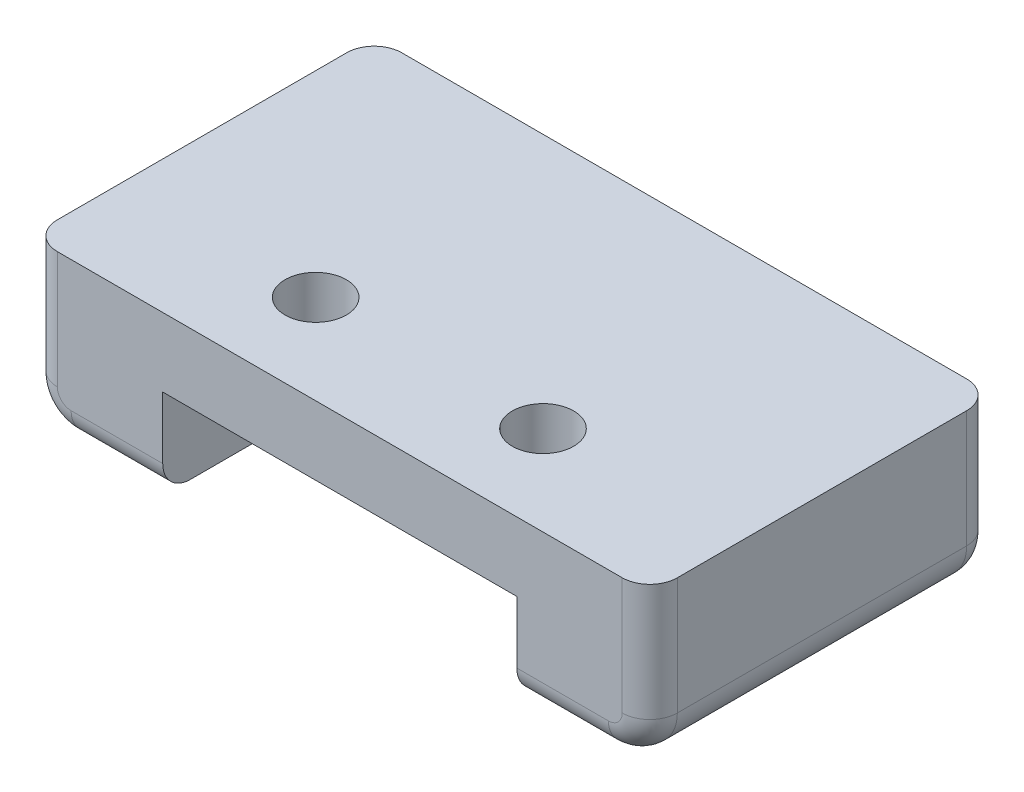
SolidWorks part; units mm, degrees
material "ABS"
ref_plane "Front Plane" through (0, 0, 0) normal (0, 0, 1) x (1, 0, 0)
ref_plane "Top Plane" through (0, 0, 0) normal (0, 1, 0) x (1, 0, 0)
ref_plane "Right Plane" through (0, 0, 0) normal (1, 0, 0) x (0, 0, -1)
sketch "Sketch1" plane through (0, 0, 0) normal (0, 0, 1) x (1, 0, 0)
  line L0 (-22.5, 5) -> (22.5, 5)
  line L1 (22.5, 5) -> (22.5, -6.5)
  line L2 (22.5, -6.5) -> (12.85, -6.5)
  line L3 (12.85, -6.5) -> (12.85, 0)
  line L4 (12.85, 0) -> (-12.85, 0)
  line L5 (-12.85, 0) -> (-12.85, -6.5)
  line L6 (-12.85, -6.5) -> (-22.5, -6.5)
  line L7 (-22.5, -6.5) -> (-22.5, 5)
  line L8 (0, 0) -> (0, 5) construction
  dimension "D1" = 5
  dimension "D2" = 25.7
  dimension "D3" = 45
  dimension "D4" = 6.5
extrude "Boss-Extrude1" add sketch "Sketch1" along normal blind 25
sketch "Sketch2" plane through (0, 5, 0) normal (0, 1, 0) x (1, 0, 0)
  line L0 (0, 0) -> (0, -25) construction
  line L1 (22.5, 0) -> (-22.5, 0) construction
  line L2 (22.5, -25) -> (-22.5, -25) construction
  circle A0 centre (-8.25, -18.5) radius 2.225
  circle A1 centre (8.25, -18.5) radius 2.225
  point P10 (0, -12.5)
  dimension "D1" = 4.45
  dimension "D2" = 16.5
  dimension "D3" = 6
extrude "Cut-Extrude1" cut sketch "Sketch2" against normal through all
fillet "Fillet1" radius 3 2 edges at (22.5, -6.5, 12.5) (-22.5, -6.5, 12.5)
fillet "Fillet2" radius 2 12 edges at (16.175, -6.5, 25) (21.6213, -5.6213, 25) (-16.175, -6.5, 25) (-21.6213, -5.6213, 25) (-16.175, -6.5, 0) (-21.6213, -5.6213, 0) (16.175, -6.5, 0) (21.6213, -5.6213, 0) (22.5, 0.75, 25) (-22.5, 0.75, 25) (-22.5, 0.75, 0) (22.5, 0.75, 0)
equation "\"D2@Sketch1\"=25.5mm+\"print_fit@Parameters@Parameters.SLDPRT\""
equation "\"D1@Sketch2\"=4.00mm+\"print_free@Parameters@Parameters.SLDPRT\""
